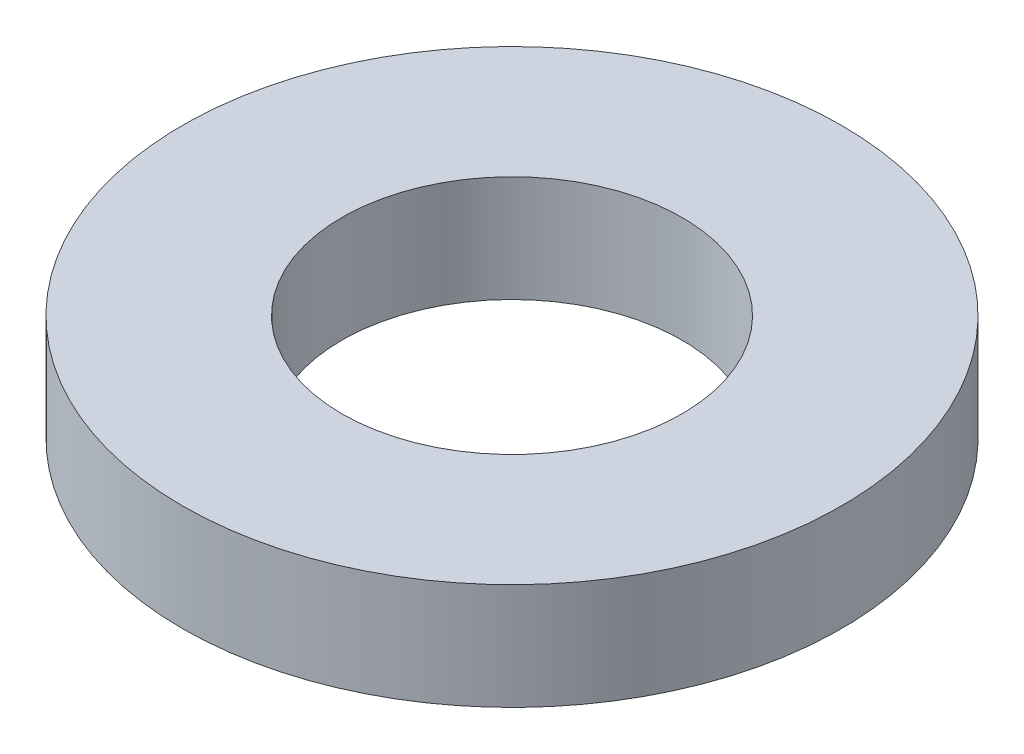
SolidWorks part; units mm, degrees
ref_plane "前视基准面" through (0, 0, 0) normal (0, 0, 1) x (1, 0, 0)
ref_plane "上视基准面" through (0, 0, 0) normal (0, 1, 0) x (1, 0, 0)
ref_plane "右视基准面" through (0, 0, 0) normal (1, 0, 0) x (0, 0, -1)
sketch "草图1" plane through (0, 0, 0) normal (0, 1, 0) x (1, 0, 0)
  circle A0 centre (0, 0) radius 1.6
  circle A2 centre (0, 0) radius 3.1
  dimension "D1" = 1.5
  dimension "D2" = 3.2
extrude "凸台-拉伸1" add sketch "草图1" along normal blind 1
